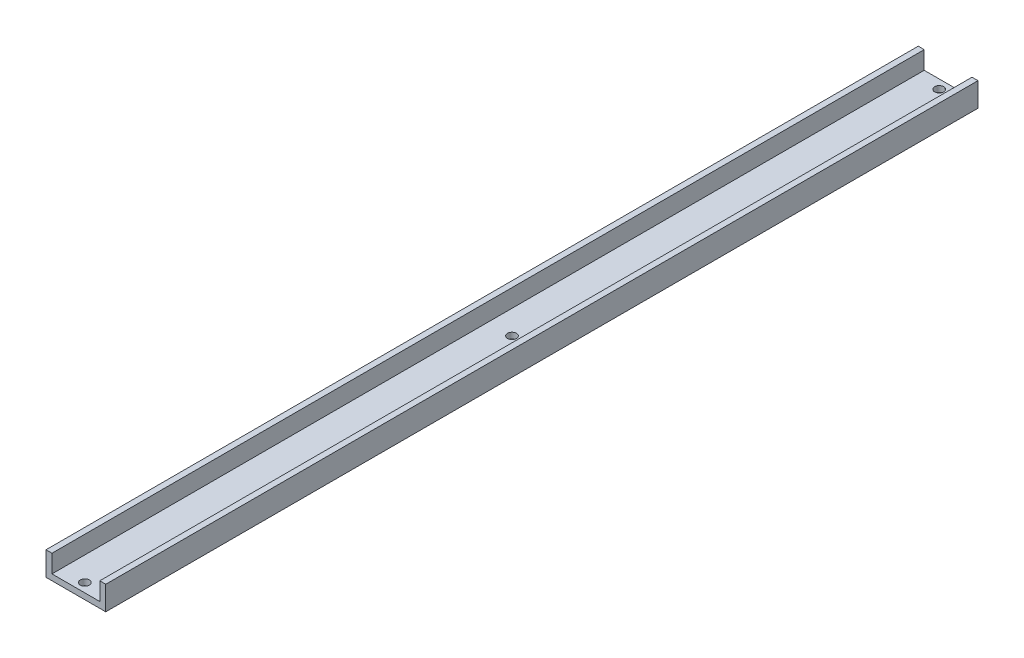
SolidWorks part; units mm, degrees
ref_plane "Front Plane" through (0, 0, 0) normal (0, 0, 1) x (1, 0, 0)
ref_plane "Top Plane" through (0, 0, 0) normal (0, 1, 0) x (1, 0, 0)
ref_plane "Right Plane" through (0, 0, 0) normal (1, 0, 0) x (0, 0, -1)
sketch "Sketch1" plane through (0, 0, 0) normal (0, 0, 1) x (1, 0, 0)
  line L0 (3.175, 3.175) -> (3.175, 12.7)
  line L1 (0, 0) -> (31.75, 0)
  line L2 (0, 0) -> (0, 12.7)
  line L4 (31.75, 0) -> (31.75, 12.7)
  line L5 (3.175, 3.175) -> (28.575, 3.175)
  line L6 (28.575, 3.175) -> (28.575, 12.7)
  line L7 (0, 12.7) -> (3.175, 12.7)
  line L8 (31.75, 12.7) -> (28.575, 12.7)
  dimension "D1" = 31.75
  dimension "D2" = 12.7
  dimension "D3" = 3.175
extrude "Boss-Extrude1" add sketch "Sketch1" along normal blind 463.55
sketch "Sketch2" plane through (0, 3.175, 0) normal (0, 1, 0) x (1, 0, 0)
  line L0 (15.875, -463.55) -> (15.875, -458.7875) construction
  line L1 (28.575, -463.55) -> (3.175, -463.55) construction
  line L2 (15.875, 0) -> (15.875, -4.7625) construction
  line L3 (28.575, 0) -> (3.175, 0) construction
  circle A0 centre (15.875, -458.7875) radius 2.413
  circle A1 centre (15.875, -4.7625) radius 2.413
  dimension "D2" = 4.826
  dimension "D4" = 4.826
  dimension "D1" = 4.7625
  dimension "D3" = 4.7625
extrude "Cut-Extrude1" cut sketch "Sketch2" against normal up to next
sketch "Sketch3" plane through (0, 3.175, 0) normal (0, 1, 0) x (1, 0, 0)
  line L0 (28.575, -231.775) -> (15.875, -231.775) construction
  line L1 (28.575, -463.55) -> (28.575, 0) construction
  circle A0 centre (15.875, -231.775) radius 2.413
  dimension "D2" = 4.826
  dimension "D1" = 12.7
extrude "Cut-Extrude2" cut sketch "Sketch3" against normal up to next
sketch "Sketch4" plane through (0, 3.175, 0) normal (0, 1, 0) x (1, 0, 0)
  line L0 (15.875, -463.55) -> (15.875, -347.6625) construction
  line L1 (28.575, -463.55) -> (3.175, -463.55) construction
  line L2 (15.875, -347.6625) -> (15.875, -231.775) construction
  line L3 (15.875, -231.775) -> (15.875, -115.8875) construction
  line L4 (15.875, -115.8875) -> (15.875, 0) construction
  line L5 (28.575, 0) -> (3.175, 0) construction
  line L6 (3.175, -463.55) -> (3.175, 0) construction
  circle A0 centre (15.875, -347.6625) radius 2.413
  circle A2 centre (15.875, -115.8875) radius 2.413
  dimension "D2" = 4.826
  dimension "D3" = 4.826
  dimension "D1" = 12.7
extrude "Cut-Extrude3" [suppressed] cut sketch "Sketch4" against normal up to next
